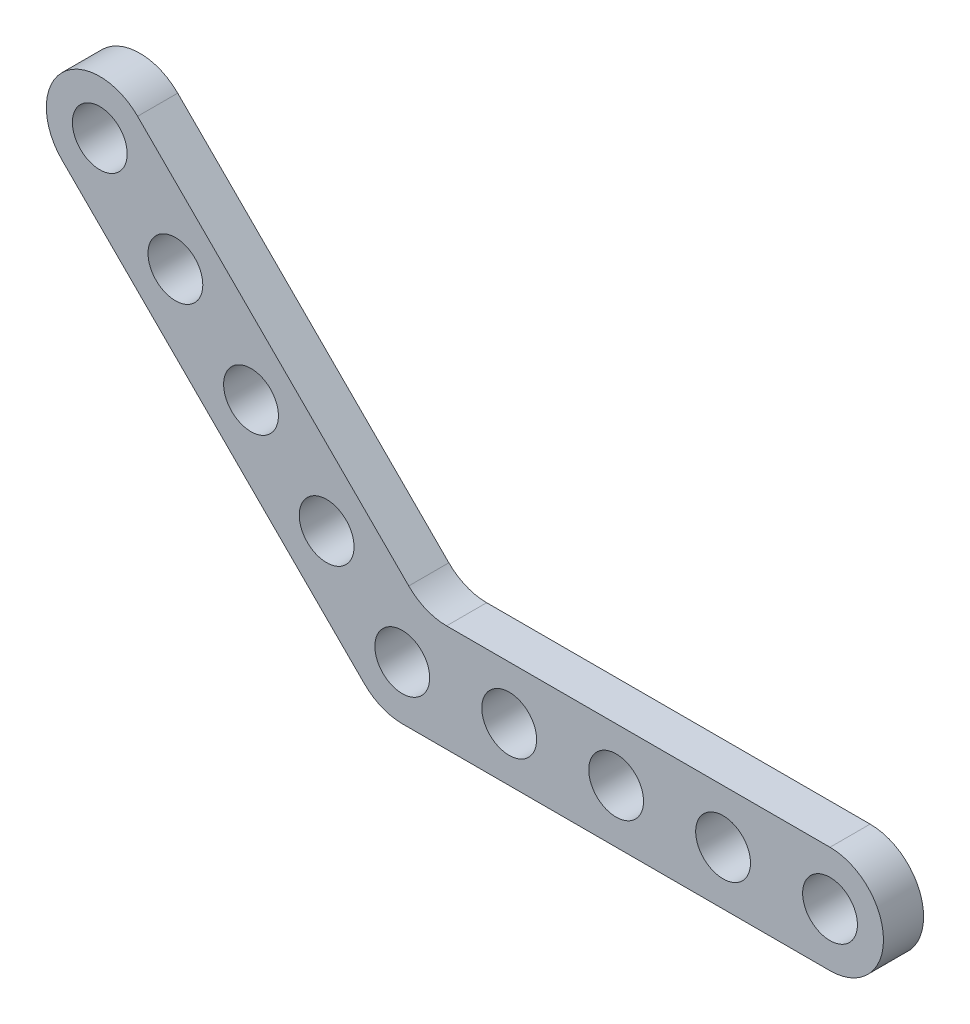
SolidWorks part; units mm, degrees
ref_plane "Front Plane" through (0, 0, 0) normal (0, 0, 1) x (1, 0, 0)
ref_plane "Top Plane" through (0, 0, 0) normal (0, 1, 0) x (1, 0, 0)
ref_plane "Right Plane" through (0, 0, 0) normal (1, 0, 0) x (0, 0, -1)
sketch "Sketch1" plane through (0, 0, 0) normal (0, 0, 1) x (1, 0, 0)
  line L0 (0, 0) -> (32, 0) construction
  line L1 (3.3137, 4) -> (32, 4)
  line L2 (0, -4) -> (32, -4)
  line L3 (0, 0) -> (-22.6274, 22.6274) construction
  line L4 (-2.8284, -2.8284) -> (-25.4558, 19.799)
  line L5 (0.4853, 5.1716) -> (-19.799, 25.4558)
  arc A0 (-2.8284, -2.8284) -> (0, -4) centre (0, 0) ccw
  arc A1 (32, -4) -> (32, 4) centre (32, 0) ccw
  arc A3 (-19.799, 25.4558) -> (-25.4558, 19.799) centre (-22.6274, 22.6274) ccw
  arc A4 (3.3137, 4) -> (0.4853, 5.1716) centre (3.3137, 8) cw
  point P4 (0, 0)
  point P8 (8.2178, 11.6434)
  point P13 (0, 0)
  point P15 (-2.8284, 15.9358)
  dimension "D1" = 4
  dimension "D2" = 4
  dimension "D6" = 4
  dimension "D3" = 32
  dimension "D4" = 32
  dimension "D5" = 135
extrude "Boss-Extrude1" add sketch "Sketch1" along normal blind 3
sketch "Sketch2" plane through (0, 0, 3) normal (0, 0, 1) x (1, 0, 0)
  line L1 (-19.799, 25.4558) -> (-25.4558, 19.799) construction
  circle A0 centre (-22.6274, 22.6274) radius 2.05
  dimension "D1" = 4.1
extrude "Cut-Extrude1" cut sketch "Sketch2" against normal through all
pattern_linear "LPattern1" count 5 spacing 8 along (0.7071, -0.7071, 0) of "Cut-Extrude1"
sketch "Sketch3" plane through (0, 0, 3) normal (0, 0, 1) x (1, 0, 0)
  circle A0 centre (32, 0) radius 2.05
  dimension "D1" = 4.1
extrude "Cut-Extrude2" cut sketch "Sketch3" against normal through all
pattern_linear "LPattern2" count 5 spacing 8 along (-1, 0, 0) of "Cut-Extrude2"
